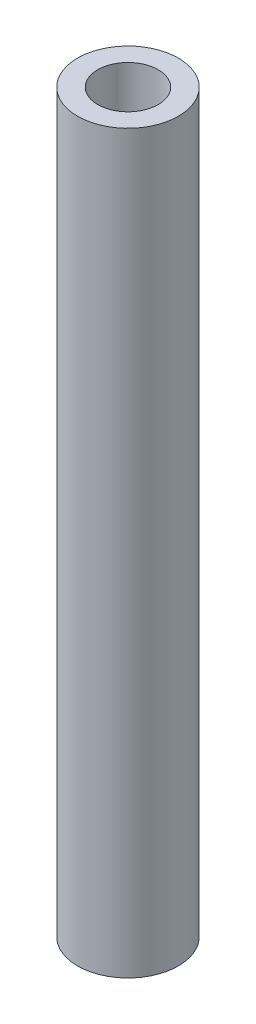
SolidWorks part; units mm, degrees
material "1060 Alloy"
ref_plane "Front Plane" through (0, 0, 0) normal (0, 0, 1) x (1, 0, 0)
ref_plane "Top Plane" through (0, 0, 0) normal (0, 1, 0) x (1, 0, 0)
ref_plane "Right Plane" through (0, 0, 0) normal (1, 0, 0) x (0, 0, -1)
sketch "Sketch1" plane through (0, 0, 0) normal (0, 1, 0) x (1, 0, 0)
  circle A0 centre (0, 0) radius 3
  circle A1 centre (0, 0) radius 5
extrude "Boss-Extrude1" add sketch "Sketch1" along normal blind 73
